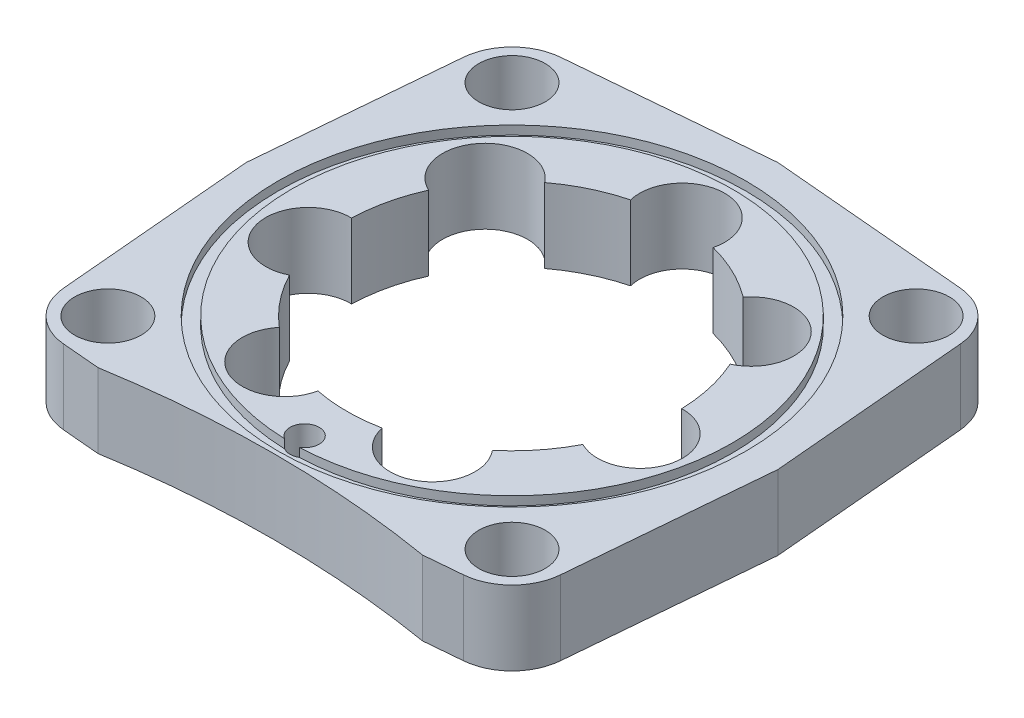
SolidWorks part; units mm, degrees
ref_plane "Front Plane" through (0, 0, 0) normal (0, 0, 1) x (1, 0, 0)
ref_plane "Top Plane" through (0, 0, 0) normal (0, 1, 0) x (1, 0, 0)
ref_plane "Right Plane" through (0, 0, 0) normal (1, 0, 0) x (0, 0, -1)
sketch "Sketch1" plane through (0, 0, 0) normal (0, 1, 0) x (1, 0, 0)
  line L0 (0, 50) -> (0, -50) construction
  line L1 (-50, -50) -> (50, -50)
  line L2 (-50, -50) -> (-50, 50)
  line L3 (-50, 50) -> (50, 50)
  line L4 (50, -50) -> (50, 50)
  line L6 (-50, 50) -> (50, -50) construction
  line L7 (-50, 0) -> (50, 0) construction
  line L8 (0, 0) -> (-25.0186, 19.9517) construction
  line L9 (0, 0) -> (25.0186, 19.9517) construction
  line L16 (-50, -50) -> (50, 50) construction
  circle A8 centre (0, 0) radius 53.75 construction
  circle A28 centre (0, 0) radius 32 construction
  arc A29 (7.7622, 30.0641) -> (-7.7622, 30.0641) centre (0, 32) ccw
  arc A31 (27.5831, -14.2575) -> (31.0376, 0.8777) centre (31.1977, -7.1207) ccw
  arc A32 (6.0508, -30.4547) -> (20.0379, -23.7189) centre (13.8843, -28.831) ccw
  arc A33 (-20.0379, -23.7189) -> (-6.0508, -30.4547) centre (-13.8843, -28.831) ccw
  arc A34 (-31.0376, 0.8777) -> (-27.5831, -14.2575) centre (-31.1977, -7.1207) ccw
  arc A35 (-18.6654, 24.8134) -> (-28.3447, 12.6759) centre (-25.0186, 19.9517) ccw
  arc A36 (-7.7622, 30.0641) -> (-18.6654, 24.8134) centre (0, 0) ccw
  arc A37 (-28.3447, 12.6759) -> (-31.0376, 0.8777) centre (0, 0) ccw
  arc A38 (-27.5831, -14.2575) -> (-20.0379, -23.7189) centre (0, 0) ccw
  arc A39 (-6.0508, -30.4547) -> (6.0508, -30.4547) centre (0, 0) ccw
  arc A40 (20.0379, -23.7189) -> (27.5831, -14.2575) centre (0, 0) ccw
  arc A41 (31.0376, 0.8777) -> (28.3447, 12.6759) centre (0, 0) ccw
  arc A42 (28.3447, 12.6759) -> (18.6654, 24.8134) centre (25.0186, 19.9517) ccw
  arc A43 (17.4273, 17.4273) -> (18.764, 14.9638) centre (25.0186, 19.9517) ccw [skipped]
  circle A44 centre (0, 0) radius 39 construction
  circle A45 centre (0, -39) radius 2.75
  arc A46 (18.6654, 24.8134) -> (7.7622, 30.0641) centre (0, 0) ccw
  point P0 (0, 0)
  point P50 (0, 0)
  dimension "D4" = 107.5
  dimension "D6" = 64
  dimension "D7" = 16
  dimension "D8" = 7
  dimension "D9" = 51.429
  dimension "D11" = 62.1
  dimension "D12" = 8
  dimension "D13" = 32
  dimension "D15" = 78
  dimension "D16" = 5.5
  dimension "D1" = 100
  dimension "D2" = 100
  dimension "D10" = 51.429
  dimension "D14" = 32
extrude "Boss-Extrude1" add sketch "Sketch1" along normal blind 14
sketch "Sketch2" plane through (0, 14, 0) normal (0, 1, 0) x (1, 0, 0)
  circle A0 centre (0, 0) radius 44
  circle A1 centre (0, 0) radius 41.4
  dimension "D1" = 82.8
  dimension "D2" = 88
extrude "Cut-Extrude1" cut sketch "Sketch2" against normal blind 1.65
sketch "Sketch3" plane through (0, 14, 0) normal (0, 1, 0) x (1, 0, 0)
  line L0 (0, 50) -> (-37.6184, 46.7088)
  line L1 (50, 50) -> (-50, 50) construction
  line L2 (0, 50) -> (37.6184, 46.7088)
  line L4 (-50, -50) -> (50, -50) construction
  line L6 (-50, 0) -> (-46.7088, 37.6184)
  line L7 (-50, 50) -> (-50, -50) construction
  line L8 (-50, 0) -> (-46.7088, -37.6184)
  line L9 (50, 0) -> (46.7088, 37.6184)
  line L10 (50, -50) -> (50, 50) construction
  line L11 (50, 0) -> (46.7088, -37.6184)
  line L12 (-45.9775, 45.9775) -> (45.9775, -45.9775) construction
  line L13 (45.9775, 45.9775) -> (-45.9775, -45.9775) construction
  line L16 (0, 50) -> (0, -50) construction
  line L17 (-50, 0) -> (50, 0) construction
  line L24 (30.5, -47.3316) -> (37.6184, -46.7088)
  line L26 (-30.5, -47.3316) -> (-37.6184, -46.7088)
  circle A1 centre (0, 0) radius 53.75 construction
  arc A7 (-46.7088, 37.6184) -> (-37.6184, 46.7088) centre (-36.7469, 36.7469) cw
  arc A8 (46.7088, 37.6184) -> (37.6184, 46.7088) centre (36.7469, 36.7469) ccw
  circle A9 centre (-38, 38) radius 6.25
  circle A10 centre (38, 38) radius 6.25
  circle A11 centre (38, -38) radius 6.25
  circle A12 centre (-38, -38) radius 6.25
  arc A13 (-46.7088, -37.6184) -> (-37.6184, -46.7088) centre (-36.7469, -36.7469) ccw
  arc A14 (46.7088, -37.6184) -> (37.6184, -46.7088) centre (36.7469, -36.7469) cw
  arc A16 (-30.5, -47.3316) -> (30.5, -47.3316) centre (0, -229.7938) cw
  arc A18 (-6.0508, -30.4547) -> (6.0508, -30.4547) centre (0, 0) ccw construction
  arc A19 (1.3831, -41.3769) -> (-1.3831, -41.3769) centre (0, -39) ccw construction
  circle A20 centre (0, 0) radius 44 construction
  dimension "D9" = 38
  dimension "D10" = 107.5
  dimension "D11" = 38
  dimension "D13" = 13.75
  dimension "D15" = 0.8
  dimension "D3" = 10
  dimension "D4" = 12.5
  dimension "D8" = 5.8
  dimension "D1" = 5
  dimension "D2" = 5
  dimension "D5" = 5
  dimension "D6" = 61
  dimension "D7" = 5
  dimension "D12" = 45
  dimension "D14" = 45
  dimension "D16" = 5
  dimension "D17" = 5
extrude "Cut-Extrude2" cut sketch "Sketch3" against normal through all flip side to cut
